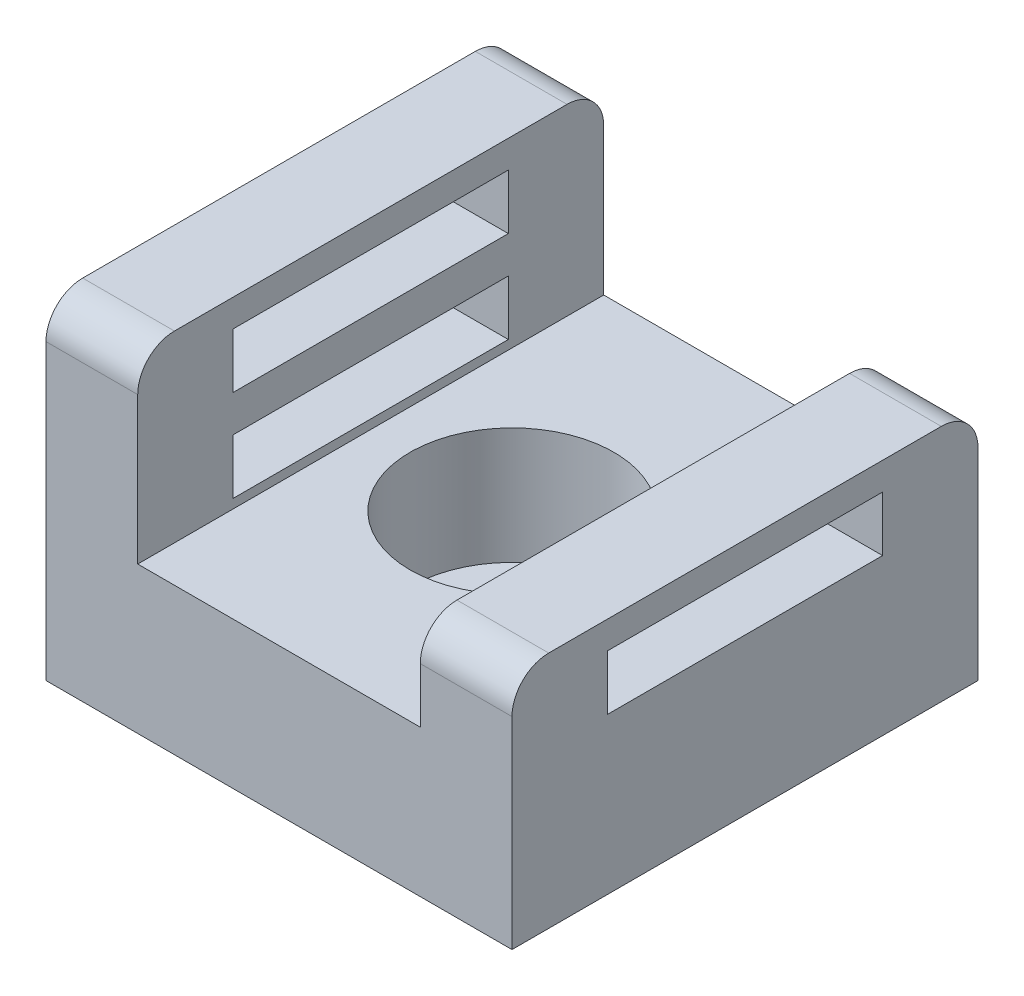
SolidWorks part; units mm, degrees
ref_plane "Front Plane" through (0, 0, 0) normal (0, 0, 1) x (1, 0, 0)
ref_plane "Top Plane" through (0, 0, 0) normal (0, 1, 0) x (1, 0, 0)
ref_plane "Right Plane" through (0, 0, 0) normal (1, 0, 0) x (0, 0, -1)
sketch "Sketch1" plane through (0, 0, 0) normal (0, 1, 0) x (1, 0, 0)
  line L1 (-10.6719, 4.8048) -> (14.7281, 4.8048)
  line L2 (-10.6719, 4.8048) -> (-10.6719, -20.5952)
  line L3 (-10.6719, -20.5952) -> (14.7281, -20.5952)
  line L4 (14.7281, 4.8048) -> (14.7281, -20.5952)
  dimension "D1" = 25.4
  dimension "D2" = 25.4
extrude "Boss-Extrude1" add sketch "Sketch1" along normal blind 8
sketch "Sketch2" plane through (0, 8, 0) normal (0, 1, 0) x (1, 0, 0)
  line L0 (-10.6719, -20.5952) -> (14.7281, -20.5952) construction
  line L1 (-10.6719, 4.8048) -> (-5.6719, 4.8048)
  line L2 (-10.6719, 4.8048) -> (-10.6719, -20.5952)
  line L3 (-10.6719, -20.5952) -> (-5.6719, -20.5952)
  line L4 (-5.6719, 4.8048) -> (-5.6719, -20.5952)
  line L6 (14.7281, 4.8048) -> (9.7281, 4.8048)
  line L7 (14.7281, 4.8048) -> (14.7281, -20.5952)
  line L8 (14.7281, -20.5952) -> (9.7281, -20.5952)
  line L9 (9.7281, 4.8048) -> (9.7281, -20.5952)
  dimension "D1" = 5
  dimension "D2" = 5
extrude "Boss-Extrude2" add sketch "Sketch2" along normal blind 5
hole_wizard "CBORE for 1/4 Socket Head Cap Screw1" positions "Sketch3" profile "Sketch4" counterbore size "1/4" standard "ANSI Inch" end condition through all
sketch "Sketch3" plane through (0, 8, 0) normal (0, 1, 0) x (1, 0, 0)
  point P0 (22.3135, -3.9437)
  point P2 (2.0281, -7.8952)
sketch "Sketch4" plane through (22.3135, 8, 3.9437) normal (1, 0, 0) x (0, 0, 1)
  line L0 (0, 0) -> (0, 8)
  line L1 (0, 8) -> (3.3782, 8)
  line L3 (3.3782, 8) -> (3.3782, 6.35)
  line L4 (3.3782, 6.35) -> (5.5562, 6.35)
  line L5 (5.5562, 6.35) -> (5.5562, 0)
  line L7 (5.5562, 0) -> (0, 0)
  line L11 (0, -6.35) -> (0, 107.95) construction
  dimension "Thru Hole Dia." = 6.7564
  dimension "Thru Hole Depth" = 8
  dimension "C'Bore Dia." = 11.1125
  dimension "C'Bore Depth" = 6.35
sketch "Sketch5" plane through (-10.6719, 0, 0) normal (-1, 0, 0) x (0, 0, 1)
  line L1 (15.3952, 8.5) -> (0.3952, 8.5)
  line L2 (15.3952, 8.5) -> (15.3952, 11.5)
  line L3 (15.3952, 11.5) -> (0.3952, 11.5)
  line L4 (0.3952, 8.5) -> (0.3952, 11.5)
  line L5 (15.3952, 8.5) -> (0.3952, 11.5) construction
  line L6 (15.3952, 11.5) -> (0.3952, 8.5) construction
  line L7 (-4.8048, 13) -> (20.5952, 13) construction
  point P0 (7.8952, 10)
  point P7 (7.8952, 13)
  dimension "D1" = 15
  dimension "D2" = 0
  dimension "D3" = 3
  dimension "D4" = 3
extrude "Cut-Extrude1" cut sketch "Sketch5" against normal through all
sketch "Sketch6" plane through (0, 13, 0) normal (0, 1, 0) x (1, 0, 0)
  line L1 (-5.6719, -20.5952) -> (-10.6719, -20.5952)
  line L2 (-5.6719, -20.5952) -> (-5.6719, 4.8048)
  line L3 (-5.6719, 4.8048) -> (-10.6719, 4.8048)
  line L4 (-10.6719, -20.5952) -> (-10.6719, 4.8048)
extrude "Boss-Extrude3" add sketch "Sketch6" along normal blind 5
sketch "Sketch7" plane through (-10.6719, 0, 0) normal (-1, 0, 0) x (0, 0, 1)
  line L0 (-4.8048, 18) -> (20.5952, 18) construction
  line L1 (0.3952, 16.5) -> (15.3952, 16.5)
  line L2 (0.3952, 16.5) -> (0.3952, 13.5)
  line L3 (0.3952, 13.5) -> (15.3952, 13.5)
  line L4 (15.3952, 16.5) -> (15.3952, 13.5)
  dimension "D1" = 1.5
  dimension "D2" = 3
extrude "Cut-Extrude2" cut sketch "Sketch7" against normal through all
fillet "Fillet1" radius 2 4 edges at (12.2281, 13, 20.5952) (12.2281, 13, -4.8048) (-8.1719, 18, -4.8048) (-8.1719, 18, 20.5952)
equation "\"SlotWidth\"=5"
equation "\"D1@Sketch2\"=\"SlotWidth\""
equation "\"D2@Sketch2\"=\"SlotWidth\""
